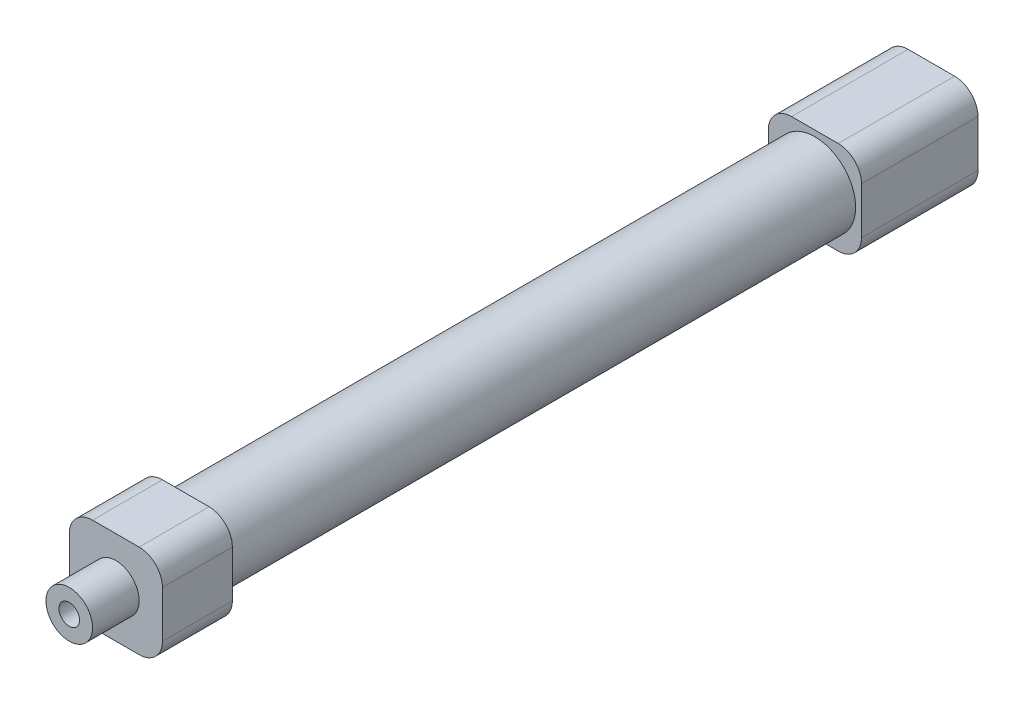
SolidWorks part; units mm, degrees
material "1023 碳钢板 (SS)"
ref_plane "前视基准面" through (0, 0, 0) normal (0, 0, 1) x (1, 0, 0)
ref_plane "上视基准面" through (0, 0, 0) normal (0, 1, 0) x (1, 0, 0)
ref_plane "右视基准面" through (0, 0, 0) normal (1, 0, 0) x (0, 0, -1)
sketch "草图1" plane through (0, 0, 0) normal (0, 0, 1) x (1, 0, 0)
  circle A0 centre (0, 0) radius 8.75
  circle A1 centre (0, 0) radius 8
  dimension "D1" = 17.5
  dimension "D2" = 16
extrude "凸台-拉伸1" add sketch "草图1" along normal blind 175
sketch "草图2" plane through (0, 0, 0) normal (0, 0, 1) x (1, 0, 0)
  line L1 (-10, -10) -> (10, -10)
  line L2 (-10, -10) -> (-10, 10)
  line L3 (-10, 10) -> (10, 10)
  line L4 (10, -10) -> (10, 10)
  line L5 (-10, -10) -> (10, 10) construction
  line L6 (-10, 10) -> (10, -10) construction
  point P0 (0, 0)
  dimension "D1" = 20
  dimension "D2" = 20
extrude "凸台-拉伸2" add sketch "草图2" along normal blind 25
sketch "草图3" plane through (0, 0, 175) normal (0, 0, 1) x (1, 0, 0)
  line L12 (10, -10) -> (10, 10)
  line L13 (10, 10) -> (-10, 10)
  line L14 (-10, 10) -> (-10, -10)
  line L15 (-10, -10) -> (10, -10)
  line L16 (10, -10) -> (10, 10)
  line L17 (10, 10) -> (-10, 10)
  line L18 (-10, 10) -> (-10, -10)
  line L19 (-10, -10) -> (10, -10)
  circle A2 centre (0, 0) radius 4
  dimension "D2" = 8
  dimension "D1" = 0
extrude "凸台-拉伸3" add sketch "草图3" against normal blind 15
fillet "圆角1" radius 5 8 edges at (10, -10, 12.5) (-10, -10, 12.5) (-10, 10, 12.5) (10, 10, 12.5) (10, -10, 167.5) (10, 10, 167.5) (-10, -10, 167.5) (-10, 10, 167.5)
sketch "草图5" plane through (0, 0, 175) normal (0, 0, 1) x (1, 0, 0)
  circle A0 centre (0, 0) radius 5
  circle A2 centre (0, 0) radius 2.2124
  dimension "D1" = 10
  dimension "6" = 4.4248
extrude "凸台-拉伸4" add sketch "草图5" along normal blind 10
